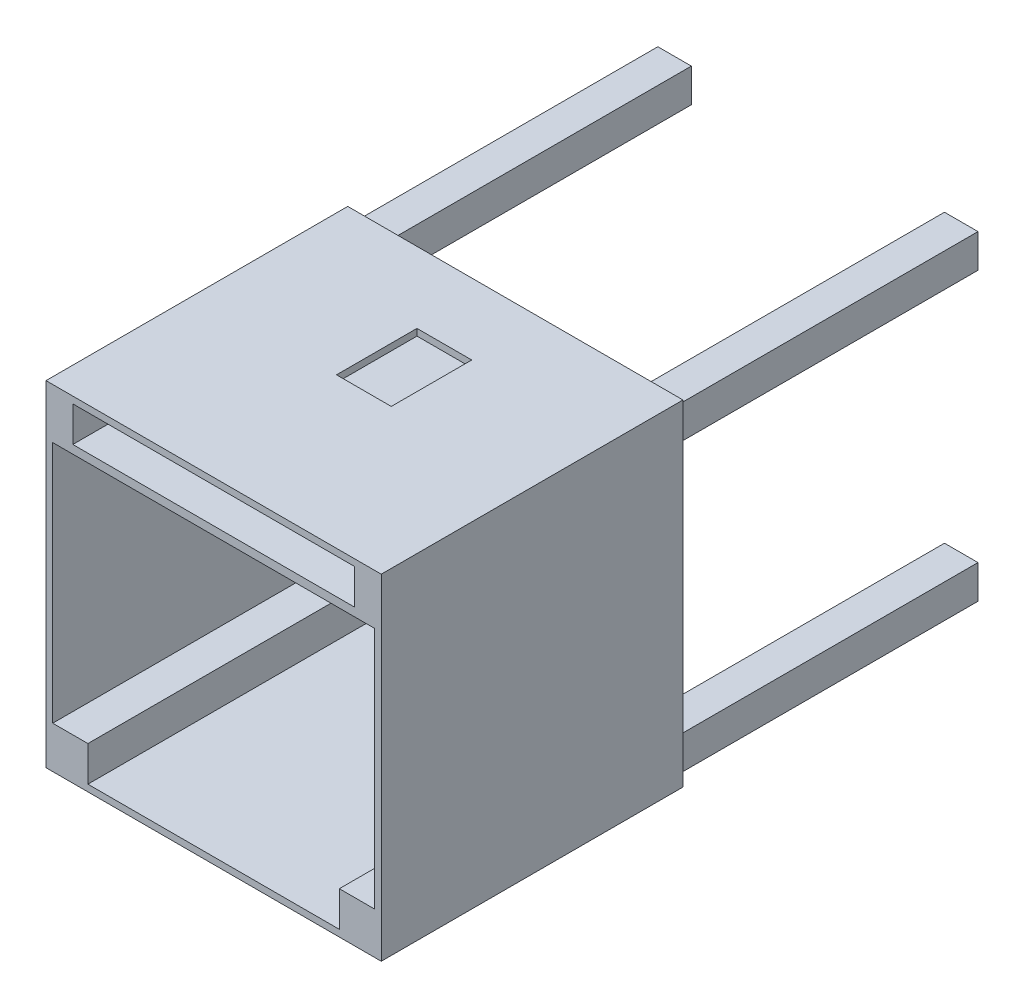
SolidWorks part; units mm, degrees
other "标注1"
sketch "草图9"
sketch "草图15" plane through (-100, -55, 220) normal (-0.5358, -0.8177, 0.2103) x (0.6424, -0.2331, 0.7301)
other "标注2"
sketch "草图10" plane through (-100, -55, 220) normal (-0.9162, -0.2658, 0.2998) x (0.0425, -0.8086, -0.5868)
sketch "草图16" plane through (-100, -55, 220) normal (-0.9162, -0.2658, 0.2998) x (0.0425, -0.8086, -0.5868)
ref_plane "前视基准面" through (0, 0, 0) normal (0, 0, 1) x (1, 0, 0)
ref_plane "上视基准面" through (0, 0, 0) normal (0, 1, 0) x (1, 0, 0)
ref_plane "右视基准面" through (0, 0, 0) normal (1, 0, 0) x (0, 0, -1)
other "Configuration Table"
sketch "草图1" plane through (0, 0, 0) normal (0, 0, 1) x (1, 0, 0)
  line L0 (-20, 0) -> (20, 0)
  line L1 (20, 0) -> (20, 90)
  line L2 (20, 90) -> (-20, 90)
  line L3 (-20, 90) -> (-20, 0)
  point P4 (0, 0)
  dimension "D1" = 40
  dimension "D2" = 90
extrude "凸台-拉伸1" add sketch "草图1" along normal blind 40
sketch "草图2" plane through (0, 0, 40) normal (0, 0, 1) x (1, 0, 0)
  line L0 (100, -55) -> (100, 145)
  line L1 (-20, 0) -> (20, 0) construction
  line L2 (0, 0) -> (0, -55) construction
  line L3 (0, 0) -> (0, 145) construction
  line L4 (100, -55) -> (-100, -55)
  line L5 (-100, -55) -> (-100, 145)
  line L6 (-100, 145) -> (100, 145)
  dimension "D1" = 145
  dimension "D2" = 55
  dimension "D3" = 100
extrude "凸台-拉伸2" add sketch "草图2" along normal blind 180
fillet "圆角3" radius 34 4 edges at (20, 45, 40) (0, 90, 40) (-20, 45, 40) (0, 0, 40)
shell "抽壳5" thickness 4
sketch "草图4" plane through (0, 0, 0) normal (0, 0, -1) x (-1, 0, 0)
  line L0 (-20, 90) -> (20, 90)
  line L1 (20, 90) -> (20, 0)
  line L2 (20, 0) -> (-20, 0)
  line L3 (-20, 0) -> (-20, 90)
sketch "草图5" plane through (0, 0, 4) normal (0, 0, 1) x (1, 0, 0)
  line L0 (-16, 86) -> (16, 86)
  line L1 (16, 86) -> (16, 4)
  line L2 (16, 4) -> (-16, 4)
  line L3 (-16, 4) -> (-16, 86)
extrude "切除-拉伸3" cut sketch "草图5" against normal blind 18
sketch "草图6" plane through (0, 0, 220) normal (0, 0, 1) x (1, 0, 0)
  line L0 (-95, 140) -> (-95, 120)
  line L1 (-95, 120) -> (-75, 120)
  line L2 (-75, 120) -> (-75, 140)
  line L3 (-75, 140) -> (-95, 140)
  line L4 (100, 145) -> (-100, 145) construction
  line L5 (-100, 145) -> (-100, -55) construction
  dimension "D1" = 5
  dimension "D2" = 5
  dimension "D3" = 20
  dimension "D4" = 20
extrude "凸台-拉伸3" add sketch "草图6" against normal blind 360
sketch "草图7" plane through (0, 0, 220) normal (0, 0, 1) x (1, 0, 0)
  line L0 (-96, 141) -> (-75, 141)
  line L2 (96, 141) -> (-96, 141) construction
  line L3 (-75, 141) -> (-75, 120)
  line L4 (-75, 120) -> (-96, 120)
  line L5 (-96, 141) -> (-96, -51) construction
  line L6 (-96, 120) -> (-96, 141)
  dimension "D3" = 21
extrude "凸台-拉伸4" add sketch "草图7" against normal blind 180
pattern_linear "阵列(线性)1" count 2 spacing 171 along (1, 0, 0) of "凸台-拉伸3", "凸台-拉伸4"
pattern_linear "阵列(线性)2" count 2 spacing 171 along (0, -1, 0) of "凸台-拉伸3", "凸台-拉伸4", "阵列(线性)1"
sketch "草图8" plane through (-20, 0, 0) normal (-1, 0, 0) x (0, 0, 1)
  line L4 (0, 20.2244) -> (0, 70.2244)
  line L5 (0, 90) -> (0, 0) construction
  line L6 (0, 70.2244) -> (10, 70.2244)
  line L7 (10, 70.2244) -> (10, 20.2244)
  line L8 (10, 20.2244) -> (0, 20.2244)
  point P4 (0, 90)
  point P7 (0, 45.2244)
  dimension "D1" = 10
  dimension "D2" = 50
extrude "凸台-拉伸8" add sketch "草图8" along direction (1, 0, 0) on the side against the normal up to surface (30 mm away) from offset 30
sketch "草图11" plane through (20, 0, 0) normal (1, 0, 0) x (0, 0, -1)
  line L0 (0, 20) -> (0, 70)
  line L1 (0, 0) -> (0, 90) construction
  line L4 (0, 70) -> (-10, 70)
  line L5 (-10, 70) -> (-10, 20)
  line L6 (-10, 20) -> (0, 20)
  point P5 (0, 45)
  point P6 (0, 45)
  dimension "D1" = 10
  dimension "D2" = 50
extrude "凸台-拉伸9" add sketch "草图11" against normal up to next from offset 30
sketch "草图12" plane through (0, 0, 0) normal (0, 0, -1) x (-1, 0, 0)
  line L0 (50, 45.2244) -> (-58.195, 45.2244) construction
  line L1 (50, 70.2244) -> (50, 20.2244) construction
  line L2 (-50, 20) -> (-50, 70) construction
  circle A0 centre (-35, 45.2244) radius 4.01
  circle A1 centre (35, 45.2244) radius 4.01
  dimension "D2" = 8.02
  dimension "D4" = 8.02
  dimension "D1" = 15
  dimension "D3" = 15
extrude "切除-拉伸4" cut sketch "草图12" against normal blind 10
sketch "草图17" plane through (0, 0, 220) normal (0, 0, 1) x (1, 0, 0)
  line L0 (-75, 120) -> (75, 120)
  line L1 (75, 120) -> (96, 120)
  line L2 (96, 120) -> (96, 115)
  line L3 (96, -30) -> (96, 120) construction
  line L4 (96, 115) -> (-96, 115)
  line L5 (-96, 120) -> (-96, -30) construction
  line L6 (-96, 115) -> (-96, 120)
  line L7 (-96, 120) -> (-75, 120)
  dimension "D1" = 5
extrude "凸台-拉伸10" add sketch "草图17" against normal up to next
sketch "草图18" plane through (0, 0, 220) normal (0, 0, 1) x (1, 0, 0)
  line L0 (75, 141) -> (84, 141)
  line L1 (75, 141) -> (75, 120)
  line L2 (75, 120) -> (84, 120)
  line L3 (84, 120) -> (84, 141)
  line L4 (-75, 141) -> (-75, 120)
  line L5 (-75, 120) -> (-84, 120)
  line L6 (-84, 120) -> (-84, 141)
  line L7 (-84, 141) -> (-75, 141)
  dimension "D1" = 9
  dimension "D2" = 9
extrude "切除-拉伸5" cut sketch "草图18" against normal blind 170
sketch "草图20" plane through (0, 145, 0) normal (0, 1, 0) x (1, 0, 0)
  line L0 (0, -40) -> (0, -306.2127) construction
  line L1 (100, -40) -> (-100, -40) construction
  line L2 (-16.33, -82.3591) -> (16.33, -82.3591)
  line L3 (16.33, -82.3591) -> (16.33, -130.3491)
  line L4 (16.33, -130.3491) -> (-16.33, -130.3491)
  line L5 (-16.33, -130.3491) -> (-16.33, -82.3591)
  point P8 (0, -82.3591)
  dimension "D2" = 32.66
  dimension "D1" = 47.99
extrude "切除-拉伸6" cut sketch "草图20" against normal blind 20
sketch "草图21" plane through (0, 0, 40) normal (0, 0, -1) x (-1, 0, 0)
  line L0 (-100, 145) -> (100, 145) construction
  circle A0 centre (0, 131) radius 7.5
  dimension "D2" = 15
  dimension "D1" = 14
extrude "切除-拉伸7" cut sketch "草图21" against normal blind 260
